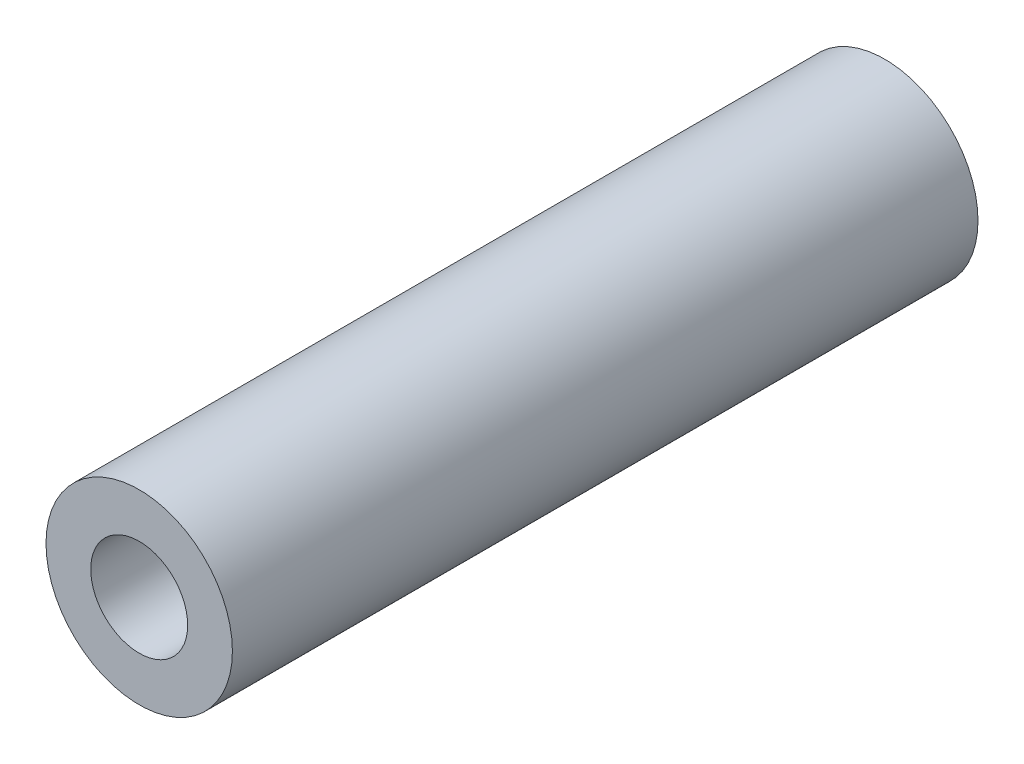
SolidWorks part; units mm, degrees
material "6061 Alloy"
ref_plane "Front Plane" through (0, 0, 0) normal (0, 0, 1) x (1, 0, 0)
ref_plane "Top Plane" through (0, 0, 0) normal (0, 1, 0) x (1, 0, 0)
ref_plane "Right Plane" through (0, 0, 0) normal (1, 0, 0) x (0, 0, -1)
sketch "Sketch1" plane through (0, 0, 0) normal (0, 0, 1) x (1, 0, 0)
  circle A0 centre (0, 0) radius 6.35
  circle A1 centre (0, 0) radius 3.302
  dimension "D1" = 12.7
  dimension "D2" = 6.604
extrude "Boss-Extrude1" add sketch "Sketch1" along normal blind 50.8
